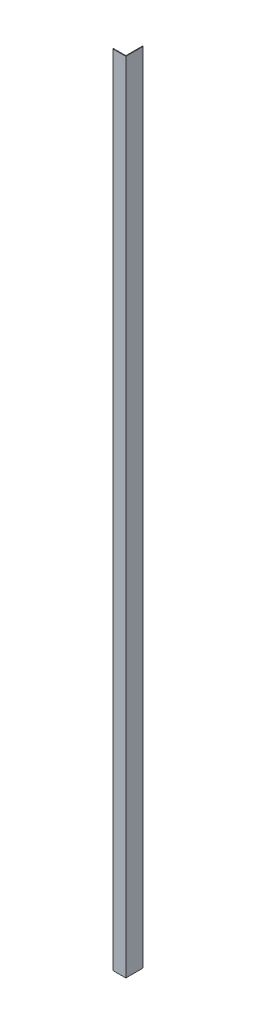
SolidWorks part; units mm, degrees
ref_plane "Front Plane" through (0, 0, 0) normal (0, 0, 1) x (1, 0, 0)
ref_plane "Top Plane" through (0, 0, 0) normal (0, 1, 0) x (1, 0, 0)
ref_plane "Right Plane" through (0, 0, 0) normal (1, 0, 0) x (0, 0, -1)
other "Configuration Table"
sketch "Sketch1" plane through (0, 0, 0) normal (0, 1, 0) x (1, 0, 0)
  line L0 (0, -40) -> (0, -38.5)
  line L1 (0, -38.5) -> (28.5, -38.5)
  line L2 (28.5, -38.5) -> (28.5, 0)
  line L3 (28.5, 0) -> (30, 0)
  line L4 (30, 0) -> (30, -40)
  line L5 (30, -40) -> (0, -40)
extrude "OVEN_sove_sol_1" add sketch "Sketch1" along normal blind 1850 from offset 120 separate body
